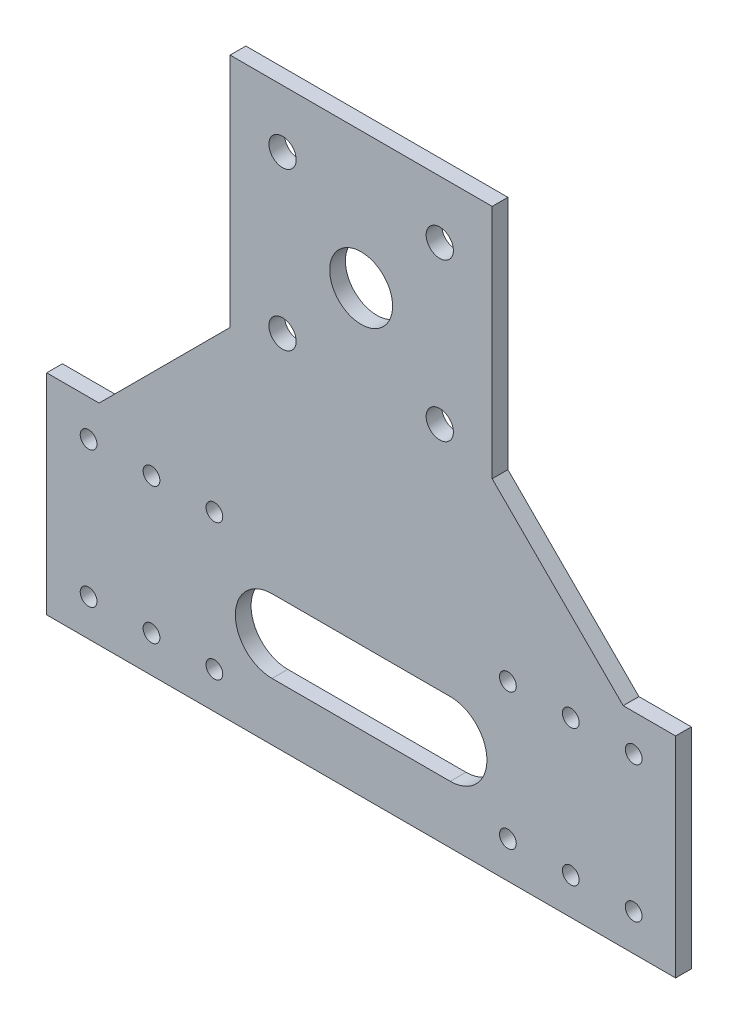
SolidWorks part; units mm, degrees
material "Thornel VCB-20 碳布"
ref_plane "前视基准面" through (0, 0, 0) normal (0, 0, 1) x (1, 0, 0)
ref_plane "上视基准面" through (0, 0, 0) normal (0, 1, 0) x (1, 0, 0)
ref_plane "右视基准面" through (0, 0, 0) normal (1, 0, 0) x (0, 0, -1)
other "Configuration Table"
sketch "草图1" plane through (0, 0, 0) normal (0, 0, 1) x (1, 0, 0)
  line L9 (0, 0) -> (0, 40)
  line L14 (0, 40) -> (10, 40)
  line L15 (10, 40) -> (35, 65)
  line L16 (35, 65) -> (35, 110)
  line L17 (35, 110) -> (85, 110)
  line L18 (85, 110) -> (85, 65)
  line L19 (85, 65) -> (110, 40)
  line L20 (110, 40) -> (120, 40)
  line L21 (120, 40) -> (120, 0)
  line L22 (120, 0) -> (0, 0)
  line L23 (35, 65) -> (85, 65) construction
  dimension "D1" = 40
  dimension "D2" = 50
  dimension "D3" = 135
  dimension "D4" = 135
  dimension "D5" = 110
  dimension "D6" = 25
  dimension "D7" = 10
extrude "凸台-拉伸1" add sketch "草图1" along normal blind 3
sketch "草图2" plane through (0, 0, 3) normal (0, 0, 1) x (1, 0, 0)
  line L0 (0, 40) -> (0, 0) construction
  line L1 (8, 33) -> (112, 33) construction
  line L2 (8, 33) -> (8, 7) construction
  line L3 (8, 7) -> (112, 7) construction
  line L4 (112, 33) -> (112, 7) construction
  line L5 (120, 0) -> (120, 40) construction
  line L6 (0, 0) -> (120, 0) construction
  line L7 (120, 40) -> (110, 40) construction
  line L8 (60, 63) -> (60, 41) construction
  line L11 (67, 63) -> (67, 41) construction
  line L12 (53, 63) -> (53, 41) construction
  line L13 (43, 18) -> (77, 18) construction
  line L14 (43, 25) -> (77, 25)
  line L15 (43, 11) -> (77, 11)
  line L16 (60, 0) -> (60, 18) construction
  circle A0 centre (45, 99) radius 2.6
  circle A1 centre (45, 99) radius 2.5
  circle A2 centre (45, 99) radius 2.5 construction
  circle A3 centre (45, 69) radius 2.5
  circle A4 centre (45, 69) radius 2.5 construction
  circle A5 centre (75, 99) radius 2.5
  circle A6 centre (75, 99) radius 2.5 construction
  circle A7 centre (75, 69) radius 2.5
  circle A8 centre (75, 69) radius 2.5 construction
  circle A9 centre (60, 84) radius 12.5
  circle A10 centre (60, 84) radius 12.5 construction
  circle A11 centre (75, 99) radius 2.6
  circle A12 centre (75, 69) radius 2.6
  circle A13 centre (45, 69) radius 2.6
  circle A14 centre (8, 33) radius 1.6
  circle A15 centre (8, 7) radius 1.6
  circle A16 centre (112, 33) radius 1.6
  circle A17 centre (112, 7) radius 1.6
  circle A18 centre (20, 33) radius 1.6
  circle A19 centre (100, 33) radius 1.6
  circle A20 centre (20, 7) radius 1.6
  circle A21 centre (100, 7) radius 1.6
  circle A22 centre (32, 33) radius 1.6
  circle A23 centre (32, 7) radius 1.6
  circle A24 centre (88, 33) radius 1.6
  circle A25 centre (88, 7) radius 1.6
  circle A28 centre (60, 84) radius 6
  arc A29 (67, 63) -> (53, 63) centre (60, 63) ccw construction
  arc A30 (53, 41) -> (67, 41) centre (60, 41) ccw construction
  circle A31 centre (40, 52) radius 7 construction
  circle A32 centre (80, 52) radius 7 construction
  arc A33 (43, 25) -> (43, 11) centre (43, 18) ccw
  arc A34 (77, 11) -> (77, 25) centre (77, 18) ccw
  point P54 (60, 52)
  point P63 (60, 18)
  dimension "D6" = 5.2
  dimension "D11" = 3.2
  dimension "D21" = 7
  dimension "D20" = 12
  dimension "D24" = 14
  dimension "D30" = 7
  dimension "D7" = 8
  dimension "D8" = 8
  dimension "D9" = 7
  dimension "D10" = 7
  dimension "D12" = 12
  dimension "D13" = 12
  dimension "D14" = 12
  dimension "D15" = 12
  dimension "D16" = 12
  dimension "D17" = 12
  dimension "D18" = 12
  dimension "D19" = 12
  dimension "D22" = 32
  dimension "D23" = 22
  dimension "D25" = 20
  dimension "D26" = 20
  dimension "D27" = 52
  dimension "D28" = 52
  dimension "D29" = 18
  dimension "D31" = 34
  dimension "D1" = 0
  dimension "D2" = 0
  dimension "D3" = 0
  dimension "D4" = 0
  dimension "D5" = 0
extrude "切除-拉伸1" cut sketch "草图2" against normal blind 10
